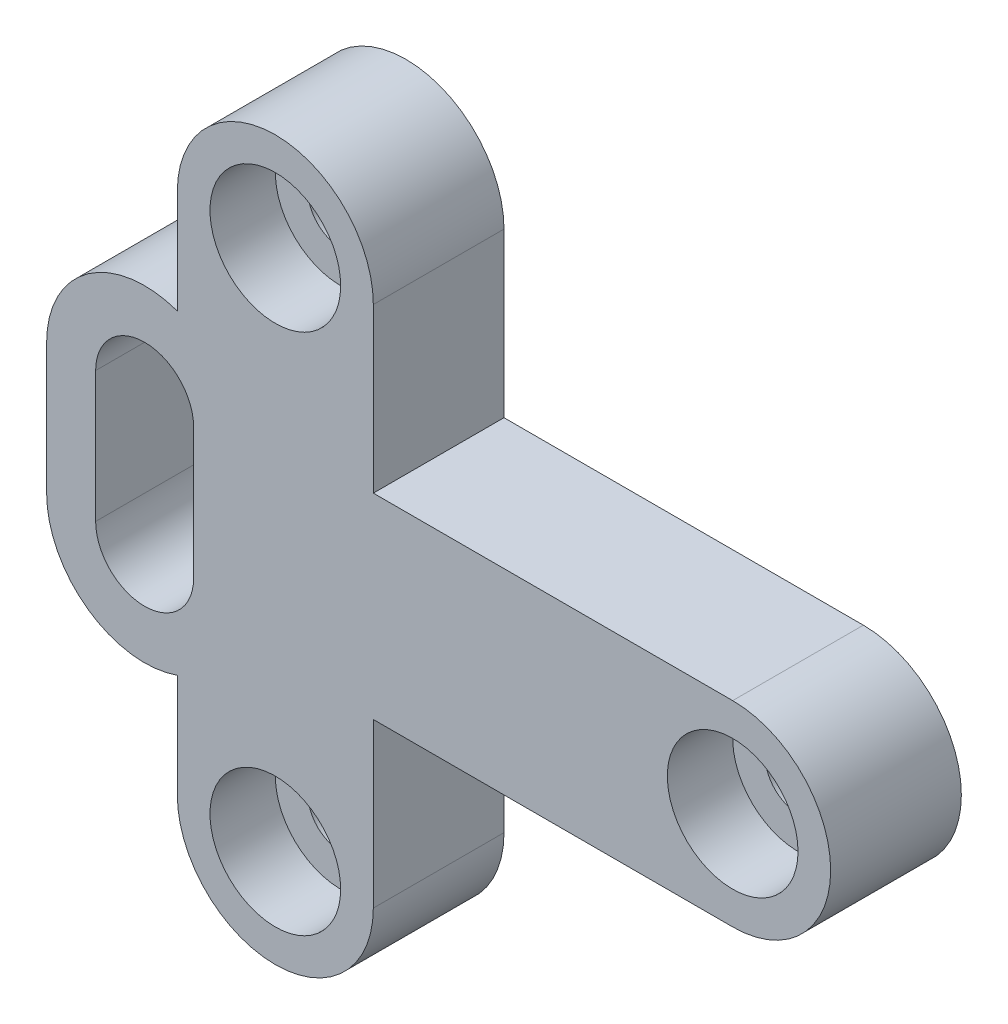
SolidWorks part; units mm, degrees
ref_plane "Front Plane" through (0, 0, 0) normal (0, 0, 1) x (1, 0, 0)
ref_plane "Top Plane" through (0, 0, 0) normal (0, 1, 0) x (1, 0, 0)
ref_plane "Right Plane" through (0, 0, 0) normal (1, 0, 0) x (0, 0, -1)
sketch "Sketch1" plane through (0, 0, 0) normal (0, 0, 1) x (1, 0, 0)
  line L0 (0, 10) -> (0, -10) construction
  line L1 (7.5, 10) -> (7.5, -10)
  line L2 (-7.5, 10) -> (-7.5, -10)
  line L3 (0, 10) -> (0, -10) construction
  line L4 (0, 10) -> (0, -10) construction
  line L6 (-15, 10) -> (-15, -10)
  line L7 (20, 40) -> (20, -40) construction
  line L8 (35, 40) -> (35, 15)
  line L9 (5, 40) -> (5, 24.1421)
  line L10 (0, 0) -> (90, 0) construction
  line L11 (5, -24.1421) -> (5, -40)
  line L12 (0, 0) -> (90, 0) construction
  line L15 (35, -15) -> (35, -40)
  line L16 (35, 15) -> (90, 15)
  line L17 (35, -15) -> (90, -15)
  arc A0 (7.5, 10) -> (-7.5, 10) centre (0, 10) ccw
  arc A1 (-7.5, -10) -> (7.5, -10) centre (0, -10) ccw
  arc A2 (5, 24.1421) -> (-15, 10) centre (0, 10) ccw
  arc A3 (-15, -10) -> (5, -24.1421) centre (0, -10) ccw
  arc A4 (35, 40) -> (5, 40) centre (20, 40) ccw
  arc A5 (5, -40) -> (35, -40) centre (20, -40) ccw
  arc A7 (90, -15) -> (90, 15) centre (90, 0) ccw
  circle A8 centre (20, 40) radius 5
  circle A9 centre (20, -40) radius 5
  circle A10 centre (90, 0) radius 5
  point P3 (0, 0)
  point P10 (0, 0)
  point P11 (45, 0)
  point P17 (20, 0)
  dimension "D2" = 7.5
  dimension "D3" = 15
  dimension "D4" = 15
  dimension "D5" = 20
  dimension "D8" = 15
  dimension "D9" = 10
  dimension "D10" = 10
  dimension "D11" = 10
  dimension "D1" = 20
  dimension "D6" = 80
  dimension "D7" = 90
extrude "Boss-Extrude1" add sketch "Sketch1" along normal blind 20
sketch "Sketch2" plane through (0, 0, 20) normal (0, 0, 1) x (1, 0, 0)
  circle A0 centre (20, 40) radius 10
  circle A1 centre (20, -40) radius 10
  circle A2 centre (90, 0) radius 10
  dimension "D1" = 20
  dimension "D2" = 20
  dimension "D3" = 20
extrude "Cut-Extrude1" cut sketch "Sketch2" against normal blind 10
